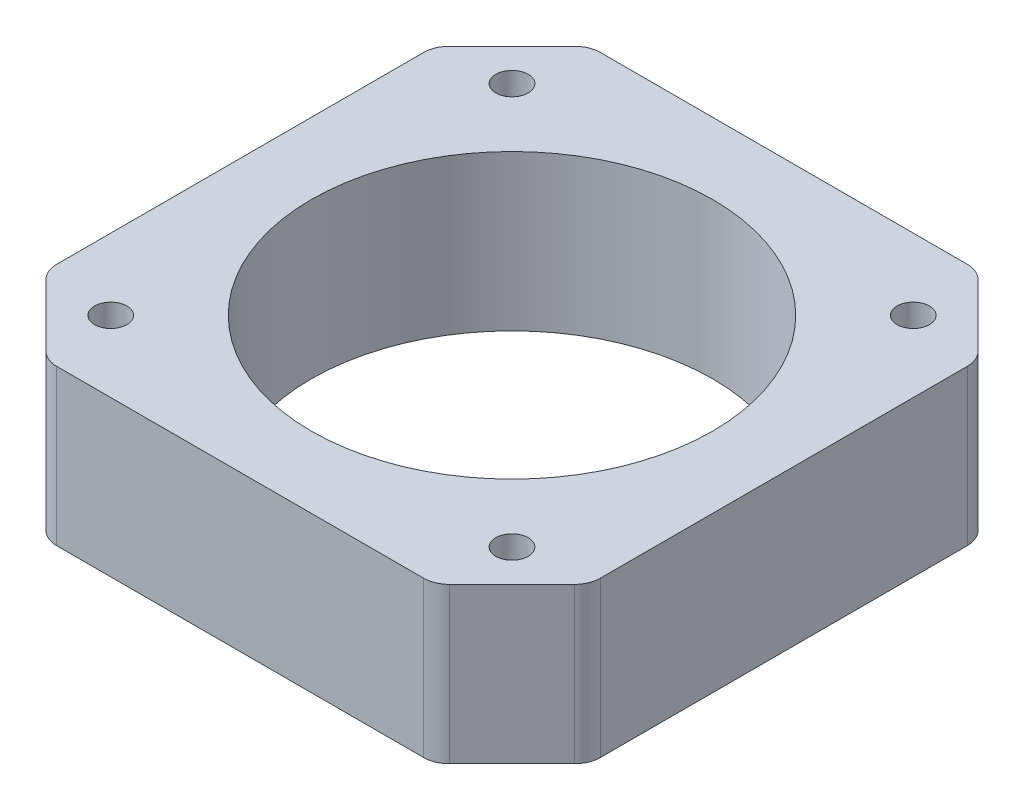
SolidWorks part; units mm, degrees
other "Camera1"
ref_plane "Front Plane" through (0, 0, 0) normal (0, 0, 1) x (1, 0, 0)
ref_plane "Top Plane" through (0, 0, 0) normal (0, 1, 0) x (1, 0, 0)
ref_plane "Right Plane" through (0, 0, 0) normal (1, 0, 0) x (0, 0, -1)
sketch "Sketch1" plane through (0, 0, 0) normal (0, 1, 0) x (1, 0, 0)
  line L0 (-15, 21.001) -> (-21, 15.001)
  line L1 (15, -21.001) -> (-15, -21.001)
  line L2 (21, -15.001) -> (21, 15.001)
  line L3 (15, 21.001) -> (-15, 21.001)
  line L4 (-21, -15.001) -> (-21, 15.001)
  line L5 (21, -21.001) -> (-21, 21.001) construction
  line L6 (21, 21.001) -> (-21, -21.001) construction
  line L7 (21, 15.001) -> (15, 21.001)
  line L8 (21, -15.001) -> (15, -21.001)
  line L9 (-15, -21.001) -> (-21, -15.001)
  circle A0 centre (0, 0) radius 15.5
  circle A1 centre (-15.5, 15.5) radius 1.25
  circle A2 centre (15.5, 15.5) radius 1.25
  circle A3 centre (-15.5, -15.5) radius 1.25
  circle A4 centre (15.5, -15.5) radius 1.25
  point P0 (0, 0)
  dimension "D1" = 42.002
  dimension "D2" = 42
extrude "Boss-Extrude2" add sketch "Sketch1" along normal blind 12
fillet "Fillet1" radius 2 8 edges at (15, 6, -21.001) (21, 6, -15.001) (21, 6, 15.001) (15, 6, 21.001) (-15, 6, 21.001) (-21, 6, 15.001) (-15, 6, -21.001) (-21, 6, -15.001)
